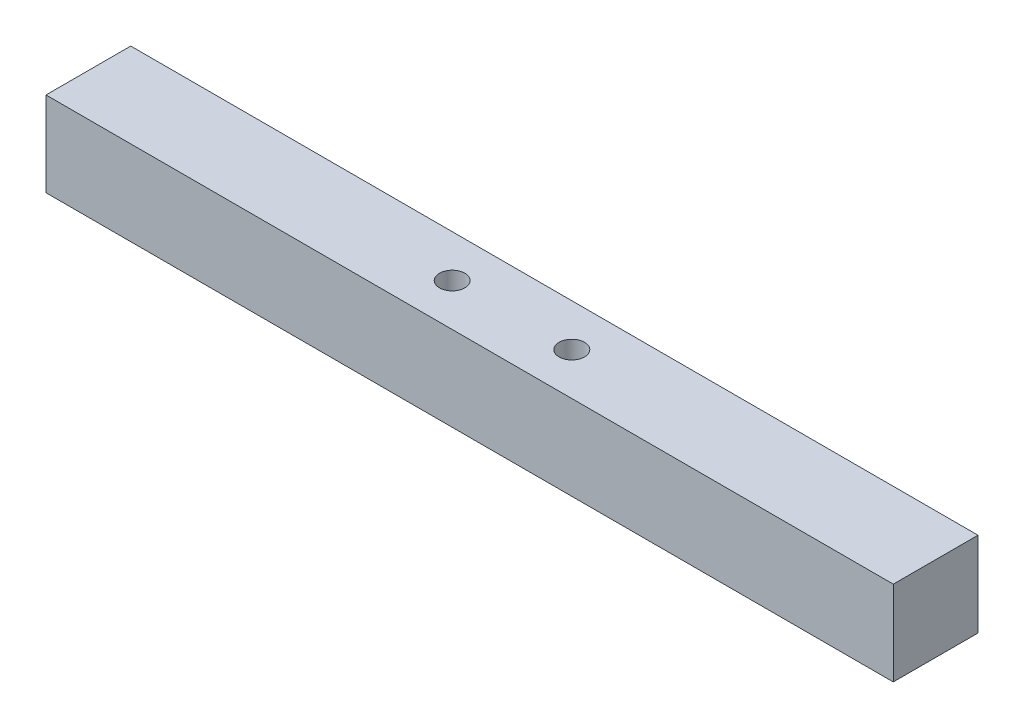
SolidWorks part; units mm, degrees
ref_plane "Front" through (0, 0, 0) normal (0, 0, 1) x (1, 0, 0)
ref_plane "Top" through (0, 0, 0) normal (0, 1, 0) x (1, 0, 0)
ref_plane "Right" through (0, 0, 0) normal (1, 0, 0) x (0, 0, -1)
sketch "Skizze1" plane through (0, 0, 0) normal (1, 0, 0) x (0, 0, -1)
  line L1 (-10, -10) -> (10, -10)
  line L2 (-10, -10) -> (-10, 10)
  line L3 (-10, 10) -> (10, 10)
  line L4 (10, -10) -> (10, 10)
  line L5 (-10, -10) -> (10, 10) construction
  line L6 (-10, 10) -> (10, -10) construction
  point P0 (0, 0)
  dimension "D1" = 20
extrude "Aufsatz-Linear austragen1" add sketch "Skizze1" along normal blind 200
sketch "Skizze2" plane through (0, 10, 0) normal (0, 1, 0) x (1, 0, 0)
  line L0 (0, 0) -> (200, 0) construction
  line L1 (0, 10) -> (0, -10) construction
  line L2 (200, 10) -> (200, -10) construction
  line L3 (100, 0) -> (100, 10) construction
  line L4 (200, 10) -> (0, 10) construction
  circle A0 centre (85.88, 0) radius 3
  circle A1 centre (114.12, 0) radius 3
  dimension "D2" = 6
  dimension "D1" = 85.88
extrude "Schnitt-Linear austragen1" cut sketch "Skizze2" against normal through all
